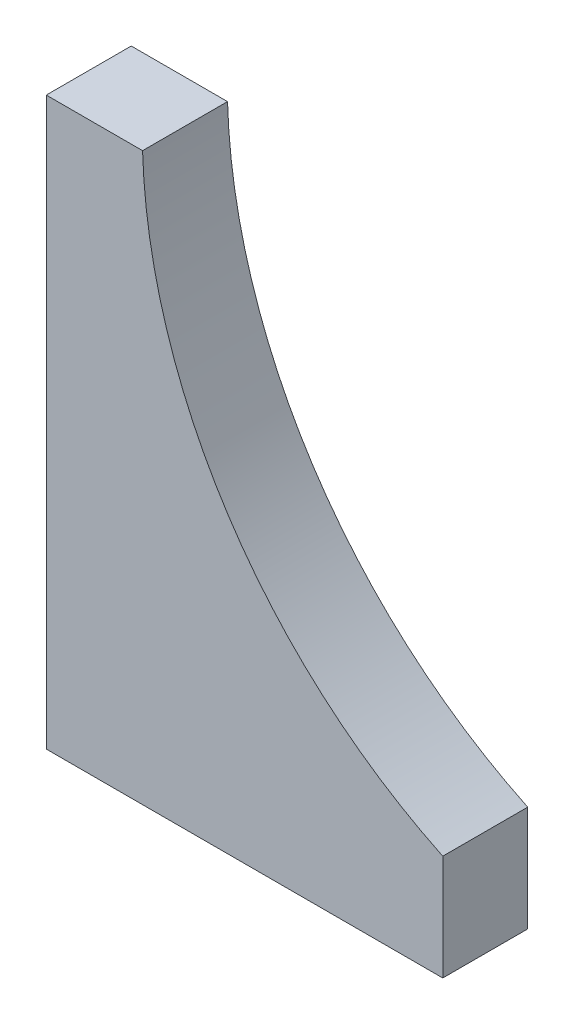
SolidWorks part; units mm, degrees
ref_plane "Plan de face" through (0, 0, 0) normal (0, 0, 1) x (1, 0, 0)
ref_plane "Plan de dessus" through (0, 0, 0) normal (0, 1, 0) x (1, 0, 0)
ref_plane "Plan de droite" through (0, 0, 0) normal (1, 0, 0) x (0, 0, -1)
sketch "Esquisse1" plane through (0, 0, 0) normal (0, 0, 1) x (1, 0, 0)
  line L0 (0, 100) -> (17, 100)
  line L1 (0, 0) -> (70, 0)
  line L2 (0, 0) -> (0, 100)
  line L4 (70, 0) -> (70, 18.6251)
  arc A1 (17, 100) -> (70, 18.6251) centre (110.2624, 102.7954) ccw
  dimension "D3" = 17
  dimension "D6" = 93.3042
  dimension "D1" = 100
  dimension "D2" = 70
  dimension "D4" = 110.2624
  dimension "D5" = 102.7954
extrude "Boss.-Extru.1" add sketch "Esquisse1" along normal blind 15
sketch "Esquisse5" plane through (0, 0, 0) normal (-1, 0, 0) x (0, 0, 1)
  line L1 (0, 100) -> (0, 0) construction
  circle A0 centre (7.5, 85) radius 2.5
  dimension "D1" = 15
  dimension "D3" = 5
  dimension "D2" = 7.5
sketch "Esquisse7" plane through (0, 0, 0) normal (-1, 0, 0) x (0, 0, 1)
  line L0 (15, 0) -> (0, 0) construction
  circle A0 centre (7.5, 25) radius 2.5
  dimension "D1" = 5
  dimension "D2" = 25
  dimension "D3" = 7.5
extrude "Enlèv. mat.-Extru.4" cut sketch "Esquisse7" against normal blind 16
extrude "Enlèv. mat.-Extru.5" cut sketch "Esquisse5" against normal blind 16
sketch "Esquisse8" plane through (0, 0, 0) normal (0, -1, 0) x (1, 0, 0)
  circle A0 centre (20, 7.5) radius 2.5
  dimension "D1" = 5
  dimension "D2" = 20
  dimension "D3" = 7.5
extrude "Enlèv. mat.-Extru.6" cut sketch "Esquisse8" against normal blind 16
sketch "Esquisse9" plane through (0, 0, 0) normal (0, -1, 0) x (1, 0, 0)
  circle A0 centre (55, 7.5) radius 2.5
  dimension "D1" = 5
  dimension "D2" = 7.5
  dimension "D3" = 15
extrude "Enlèv. mat.-Extru.7" cut sketch "Esquisse9" against normal blind 16
sketch "Esquisse10" plane through (0, 0, 15) normal (0, 0, 1) x (1, 0, 0)
  line L0 (3, 79.5) -> (15.0142, 79.5)
  line L3 (3, 97) -> (3, 90.5)
  line L4 (3, 90.5) -> (14, 90.5)
  line L5 (14, 97) -> (14, 90.5)
  line L6 (4, 18.5) -> (13.5, 18.5)
  line L7 (4, 18.5) -> (4, 4)
  line L8 (4, 4) -> (13.5, 4)
  line L9 (13.5, 18.5) -> (13.5, 4)
  line L10 (25.5, 3) -> (47.0208, 3)
  line L11 (25.5, 3) -> (25.5, 14.7395)
  line L13 (47.0208, 3) -> (47.0208, 18.3307)
  line L14 (3, 79.5) -> (3, 30.5)
  line L15 (3, 30.5) -> (19, 30.5)
  line L18 (19, 30.5) -> (19, 19)
  line L19 (19, 19) -> (25.5, 19)
  line L22 (25.5, 14.7395) -> (25.5, 19)
  line L24 (47.0208, 18.3307) -> (47.0208, 22.5912)
  line L26 (47.0208, 22.5912) -> (47.0208, 28.3734)
  line L29 (3, 97) -> (14, 97)
  line L30 (0, 82.5) -> (16, 82.5) construction
  line L31 (0, 100) -> (0, 0) construction
  line L32 (16, 27.5) -> (0, 27.5) construction
  line L33 (16, 27.5) -> (16, 22.5) construction
  line L34 (17.5, 16) -> (22.5, 16) construction
  line L35 (22.5, 0) -> (22.5, 16) construction
  line L36 (0, 0) -> (70, 0) construction
  line L37 (52.5, 16) -> (52.5, 0) construction
  line L38 (16, 87.5) -> (0, 87.5) construction
  line L39 (17, 100) -> (0, 100) construction
  line L40 (17.5, 16) -> (17.5, 0) construction
  line L41 (0, 22.5) -> (16, 22.5) construction
  arc A2 (15.0142, 79.5) -> (47.0208, 28.3734) centre (107.5815, 101.8679) ccw
  dimension "D13" = 95.2315
  dimension "D14" = 107.5815
  dimension "D1" = 3
  dimension "D2" = 3
  dimension "D3" = 3
  dimension "D4" = 3
  dimension "D5" = 3
  dimension "D6" = 3
  dimension "D7" = 3
  dimension "D8" = 5.4792
  dimension "D9" = 3
  dimension "D10" = 3
  dimension "D11" = 3
  dimension "D12" = 3
  dimension "D15" = 101.8679
  dimension "D16" = 4
  dimension "D17" = 4
  dimension "D18" = 4
  dimension "D19" = 4
extrude "Enlèv. mat.-Extru.8" cut sketch "Esquisse10" against normal blind 9 from offset 3 offset against normal yes
